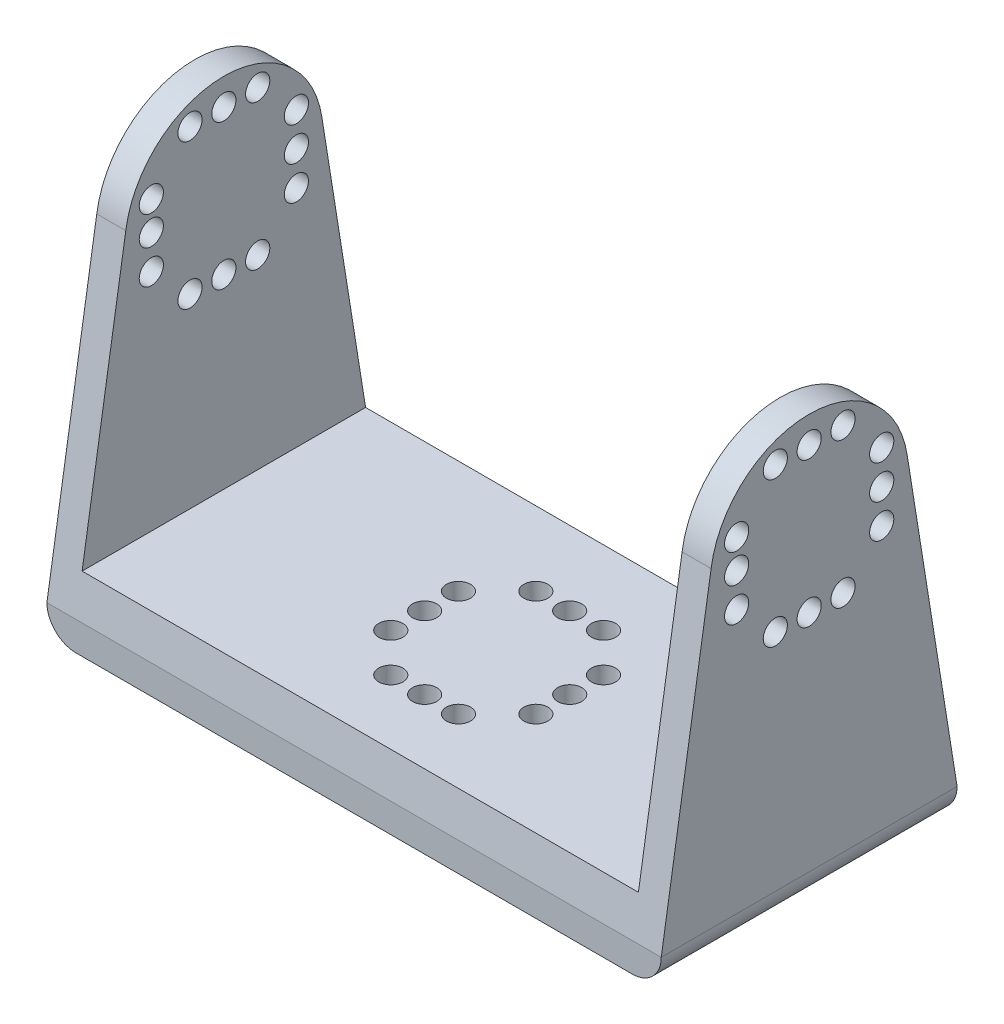
SolidWorks part; units mm, degrees
ref_plane "Front Plane" through (0, 0, 0) normal (0, 0, 1) x (1, 0, 0)
ref_plane "Top Plane" through (0, 0, 0) normal (0, 1, 0) x (1, 0, 0)
ref_plane "Right Plane" through (0, 0, 0) normal (1, 0, 0) x (0, 0, -1)
sketch "Sketch2" plane through (0, 0, 0) normal (0, 1, 0) x (1, 0, 0)
  line L1 (-52.0231, 30.2191) -> (11.4969, 30.2191)
  line L2 (-52.0231, 30.2191) -> (-52.0231, -0.3709)
  line L3 (-52.0231, -0.3709) -> (11.4969, -0.3709)
  line L4 (11.4969, 30.2191) -> (11.4969, -0.3709)
extrude "Boss-Extrude1" add sketch "Sketch2" along normal blind 7
sketch "Sketch3" plane through (0, 7, 0) normal (0, 1, 0) x (1, 0, 0)
  line L0 (-52.0231, 30.2191) -> (-49.0231, 30.2191)
  line L1 (11.4969, 30.2191) -> (-52.0231, 30.2191) construction
  line L2 (-49.0231, 30.2191) -> (-49.0231, -0.3709)
  line L3 (-52.0231, -0.3709) -> (11.4969, -0.3709) construction
  line L4 (-49.0231, -0.3709) -> (-52.0231, -0.3709)
  line L5 (-52.0231, -0.3709) -> (-52.0231, 30.2191)
  line L6 (11.4969, 30.2191) -> (8.4969, 30.2191) construction
  line L7 (8.4969, 30.2191) -> (8.4969, -0.3709) construction
  line L8 (8.4969, -0.3709) -> (11.4969, -0.3709) construction
  line L9 (11.4969, -0.3709) -> (11.4969, 30.2191) construction
  line L10 (11.4969, -0.3709) -> (11.4969, 30.2191) construction
  line L11 (8.4969, 30.2191) -> (11.4969, 30.2191)
  line L12 (11.4969, 30.2191) -> (11.4969, -0.3709)
  line L13 (11.4969, -0.3709) -> (8.4969, -0.3709)
  line L14 (8.4969, -0.3709) -> (8.4969, 30.2191)
extrude "Boss-Extrude2" add sketch "Sketch3" along normal blind 40
fillet "Fillet2" radius 3 2 edges at (11.4969, 0, -14.9241) (-52.0231, 0, -14.9241)
sketch "Sketch4" plane through (-52.0231, 0, 0) normal (-1, 0, 0) x (0, 0, 1)
  line L0 (-30.2191, 3) -> (-30.2191, 47) construction
  line L1 (-30.2191, 47) -> (-30.2191, 25) construction
  line L2 (-30.2191, 25) -> (-30.2191, 36) construction
  line L3 (-22.4241, 37.2387) -> (-22.4241, 33.7387) construction
  line L4 (-30.2191, 3) -> (-25.0219, 35.4887) construction
  line L5 (-22.4241, 33.7387) -> (-22.4241, 35.4887) construction
  line L6 (-14.9241, 33.7387) -> (-7.4241, 33.7387) construction
  line L7 (-7.4241, 33.7387) -> (-7.4241, 30.2387) construction
  line L8 (-7.4241, 33.7387) -> (-7.4241, 36.7387) construction
  line L9 (-14.9241, 33.7387) -> (-14.9241, 26.2387) construction
  line L10 (-14.9241, 26.2387) -> (-11.4241, 26.2387) construction
  line L11 (-14.9241, 26.2387) -> (-18.4241, 26.2387) construction
  line L12 (-14.9241, 33.7387) -> (-22.4241, 33.7387) construction
  line L13 (-22.4241, 33.7387) -> (-22.4241, 30.2387) construction
  line L14 (-22.4241, 33.7387) -> (-22.4241, 30.2387) construction
  line L15 (-14.9241, 33.7387) -> (-14.9241, 41.2387) construction
  line L16 (-14.9241, 41.2387) -> (-11.4241, 41.2387) construction
  line L17 (-11.4241, 41.2387) -> (-18.4241, 41.2387) construction
  line L18 (-22.4241, 35.4887) -> (-25.0219, 35.4887) construction
  line L19 (0.3709, 3) -> (-30.2191, 3) construction
  line L20 (-25.0219, 35.4887) -> (-4.8263, 35.4887) construction
  line L21 (-4.8263, 35.4887) -> (0.3709, 3) construction
  line L22 (-30.2191, 3) -> (0.3709, 3)
  line L23 (-25.0219, 35.4887) -> (-30.2191, 3)
  line L24 (-4.8263, 35.4887) -> (0.3709, 3)
  circle A0 centre (-14.9241, 33.7387) radius 10.2484
  circle A1 centre (-7.4241, 33.7387) radius 1.25
  circle A2 centre (-7.4241, 30.2387) radius 1.25
  circle A3 centre (-7.4241, 36.7387) radius 1.25
  circle A4 centre (-14.9241, 26.2387) radius 1.25
  circle A5 centre (-11.4241, 26.2387) radius 1.25
  circle A6 centre (-18.4241, 26.2387) radius 1.25
  circle A7 centre (-22.4241, 33.7387) radius 1.25
  circle A8 centre (-22.4241, 37.2387) radius 1.25
  circle A9 centre (-22.4241, 30.2387) radius 1.25
  circle A10 centre (-11.4241, 41.2387) radius 1.25
  circle A11 centre (-18.4241, 41.2387) radius 1.25
  circle A12 centre (-14.9241, 41.2387) radius 1.25
extrude "Cut-Extrude2" cut sketch "Sketch4" against normal blind 70
sketch "Sketch7" plane through (0, 0, 0) normal (0, 1, 0) x (1, 0, 0)
  line L0 (8.9219, 28.867) -> (8.9219, -0.0188) construction
  line L1 (8.9219, -0.0188) -> (-49.4481, -0.0188) construction
  line L2 (-49.4481, -0.0188) -> (-49.4481, 28.867) construction
  line L3 (-49.4481, 28.867) -> (8.9219, 28.867) construction
  line L4 (8.9219, 28.867) -> (-20.2631, 28.867) construction
  line L5 (8.9219, 14.4241) -> (-49.4481, 14.4241) construction
  line L6 (-49.4481, 14.4241) -> (-20.2631, 14.4241) construction
  line L7 (-20.2631, 14.4241) -> (-20.2631, 21.9241) construction
  line L8 (-20.2631, 14.4241) -> (-20.2631, 6.9241) construction
  line L9 (-20.2631, 14.4241) -> (-12.7631, 14.4241) construction
  line L10 (-20.2631, 14.4241) -> (-27.7631, 14.4241) construction
  line L11 (-12.7631, 14.4241) -> (-12.7631, 17.9241) construction
  line L12 (-12.7631, 14.4241) -> (-12.7631, 10.9241) construction
  line L13 (-20.2631, 6.9241) -> (-16.7631, 6.9241) construction
  line L14 (-20.2631, 6.9241) -> (-23.7631, 6.9241) construction
  line L15 (-20.2631, 21.9241) -> (-16.7631, 21.9241) construction
  line L16 (-20.2631, 21.9241) -> (-23.7631, 21.9241) construction
  line L17 (-27.7631, 14.4241) -> (-27.7631, 17.9241) construction
  line L18 (-27.7631, 14.4241) -> (-27.7631, 10.9241) construction
  circle A0 centre (-20.2631, 21.9241) radius 1.25
  circle A1 centre (-20.2631, 6.9241) radius 1.25
  circle A2 centre (-12.7631, 14.4241) radius 1.25
  circle A3 centre (-27.7631, 14.4241) radius 1.25
  circle A4 centre (-12.7631, 17.9241) radius 1.25
  circle A5 centre (-12.7631, 10.9241) radius 1.25
  circle A6 centre (-16.7631, 6.9241) radius 1.25
  circle A7 centre (-23.7631, 6.9241) radius 1.25
  circle A8 centre (-16.7631, 21.9241) radius 1.25
  circle A9 centre (-23.7631, 21.9241) radius 1.25
  circle A10 centre (-27.7631, 17.9241) radius 1.25
  circle A11 centre (-27.7631, 10.9241) radius 1.25
extrude "Cut-Extrude4" cut sketch "Sketch7" along normal blind 20 and the other way blind 6
